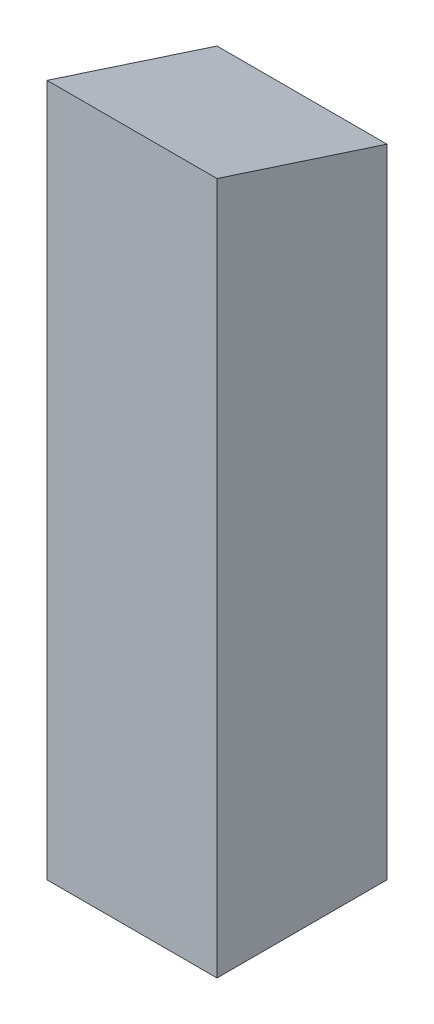
SolidWorks part; units mm, degrees
ref_plane "Front Plane" through (0, 0, 0) normal (0, 0, 1) x (1, 0, 0)
ref_plane "Top Plane" through (0, 0, 0) normal (0, 1, 0) x (1, 0, 0)
ref_plane "Right Plane" through (0, 0, 0) normal (1, 0, 0) x (0, 0, -1)
sketch "Sketch1" plane through (0, 0, 0) normal (1, 0, 0) x (0, 0, -1)
  line L0 (19.05, 68.2117) -> (0, 74.4014)
  line L1 (0, 0) -> (19.05, 0)
  line L2 (0, 0) -> (0, 68.2117)
  line L3 (0, 68.2117) -> (19.05, 68.2117)
  line L4 (19.05, 0) -> (19.05, 68.2117)
  line L5 (0, 68.2117) -> (0, 74.4014)
  line L7 (0, 0) -> (19.05, 0)
  line L8 (0, 0) -> (0, -3.175)
  line L9 (0, -3.175) -> (19.05, -3.175)
  line L10 (19.05, 0) -> (19.05, -3.175)
  dimension "D1" = 68.2117
  dimension "D2" = 19.05
  dimension "D3" = 18
  dimension "D4" = 3.175
extrude "Boss-Extrude1" add sketch "Sketch1" along normal blind 19.05 contours L5 L3 L0 | L1 L4 L3 L2 | L8 L7 L10 L9
